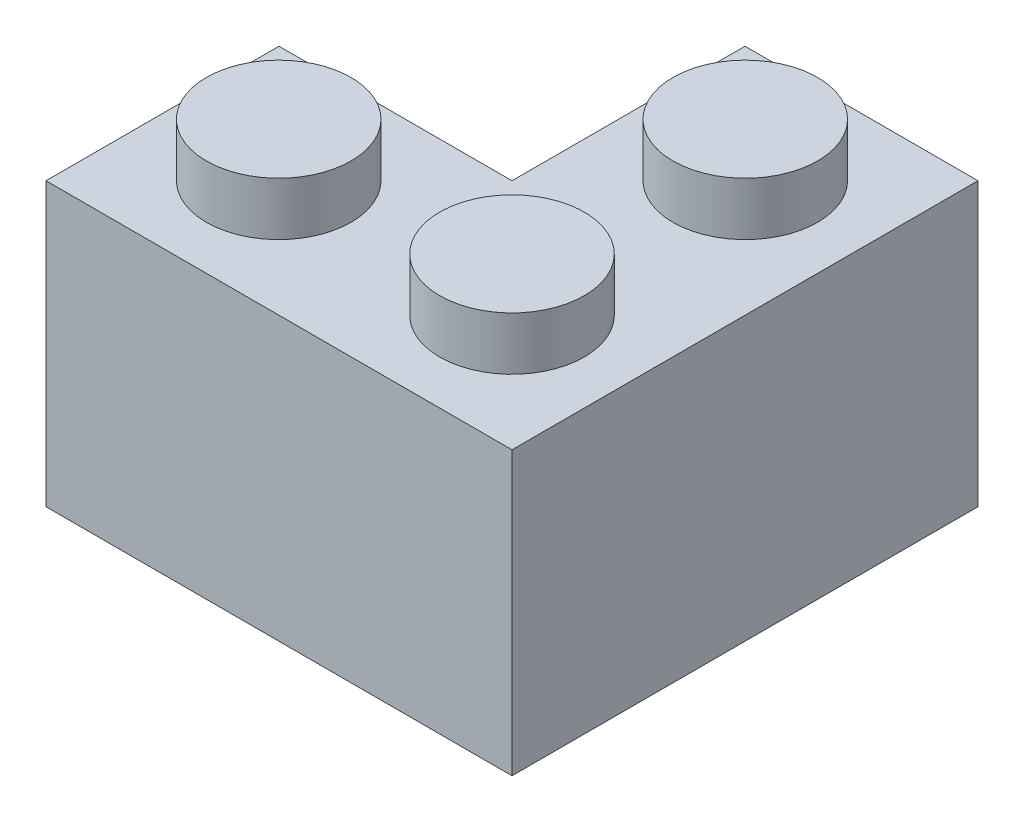
SolidWorks part; units mm, degrees
ref_plane "Front Plane" through (0, 0, 0) normal (0, 0, 1) x (1, 0, 0)
ref_plane "Top Plane" through (0, 0, 0) normal (0, 1, 0) x (1, 0, 0)
ref_plane "Right Plane" through (0, 0, 0) normal (1, 0, 0) x (0, 0, -1)
sketch "Sketch1" plane through (0, 0, 0) normal (0, 1, 0) x (1, 0, 0)
  line L0 (0, 0) -> (0, 7.89)
  line L1 (0, 7.89) -> (7.89, 7.89)
  line L2 (7.89, 7.89) -> (7.89, -7.89)
  line L3 (7.89, -7.89) -> (-7.89, -7.89)
  line L4 (-7.89, -7.89) -> (-7.89, 0)
  line L5 (-7.89, 0) -> (0, 0)
  point P6 (0, 0)
  point P8 (0, -7.89)
  point P9 (0, 0)
  point P10 (7.89, 0)
  dimension "D1" = 15.78
  dimension "D2" = 15.78
extrude "Boss-Extrude1" add sketch "Sketch1" against normal blind 9.56
sketch "Sketch2" plane through (0, 0, 0) normal (0, 1, 0) x (1, 0, 0)
  line L2 (-7.89, -7.89) -> (7.89, -7.89) construction
  line L3 (7.89, -7.89) -> (7.89, 7.89) construction
  line L5 (-7.89, 0) -> (-7.89, -7.89) construction
  circle A0 centre (3.945, -3.945) radius 2.45
  circle A1 centre (3.945, 3.955) radius 2.45
  circle A2 centre (-3.955, -3.945) radius 2.45
  dimension "D3" = 4.9
  dimension "D5" = 7.9
  dimension "D1" = 3.945
  dimension "D2" = 3.945
  dimension "D7" = 3.935
  dimension "D4" = 2
  dimension "D6" = 2
extrude "Boss-Extrude2" add sketch "Sketch2" along normal blind 1.8
shell "Shell1" thickness 1.5
sketch "Sketch3" plane through (0, -1.5, 0) normal (0, -1, 0) x (1, 0, 0)
  line L1 (-7.89, 7.89) -> (7.89, 7.89) construction
  line L3 (7.89, 7.89) -> (7.89, -7.89) construction
  circle A0 centre (0, 3.945) radius 1.48
  circle A1 centre (3.945, 0) radius 1.48
  dimension "D2" = 2.96
  dimension "D3" = 3.945
  dimension "D4" = 2.96
  dimension "D1" = 3.945
extrude "Boss-Extrude4" add sketch "Sketch3" along normal offset from surface (7.86 mm away) 0.2 up to face at (0.5, -9.56, 0.5)
